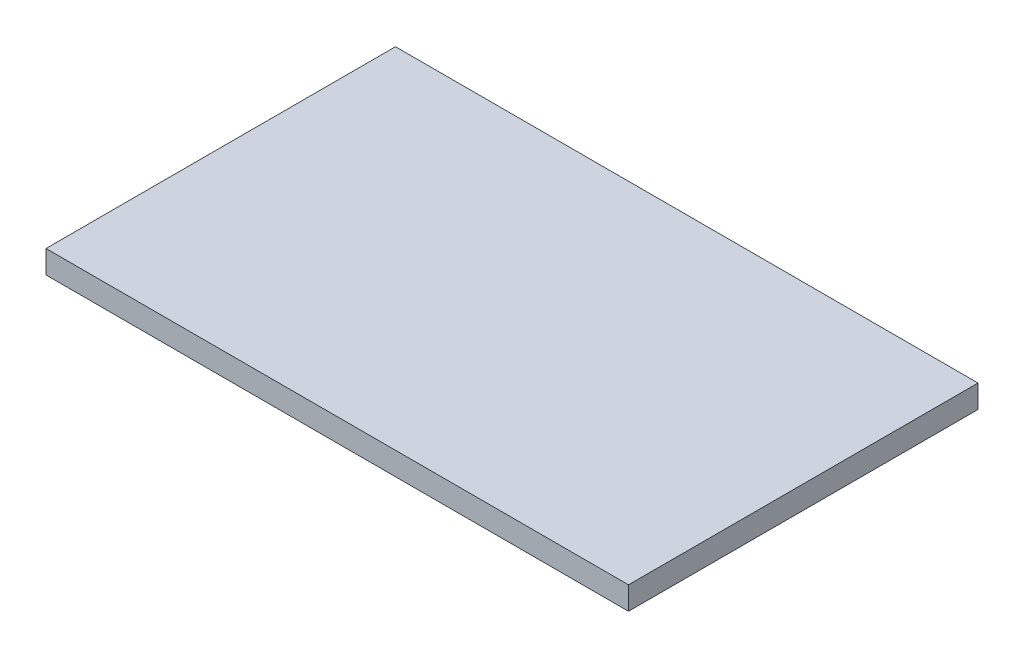
SolidWorks part; units mm, degrees
ref_plane "Front Plane" through (0, 0, 0) normal (0, 0, 1) x (1, 0, 0)
ref_plane "Top Plane" through (0, 0, 0) normal (0, 1, 0) x (1, 0, 0)
ref_plane "Right Plane" through (0, 0, 0) normal (1, 0, 0) x (0, 0, -1)
sketch "Sketch1" plane through (0, 0, 0) normal (0, 1, 0) x (1, 0, 0)
  line L1 (-254, -152.4) -> (254, -152.4)
  line L2 (-254, -152.4) -> (-254, 152.4)
  line L3 (-254, 152.4) -> (254, 152.4)
  line L4 (254, -152.4) -> (254, 152.4)
  line L5 (-254, -152.4) -> (254, 152.4) construction
  line L6 (-254, 152.4) -> (254, -152.4) construction
  point P0 (0, 0)
  dimension "D1" = 304.8
  dimension "D2" = 508
extrude "Boss-Extrude1" add sketch "Sketch1" against normal blind 20
